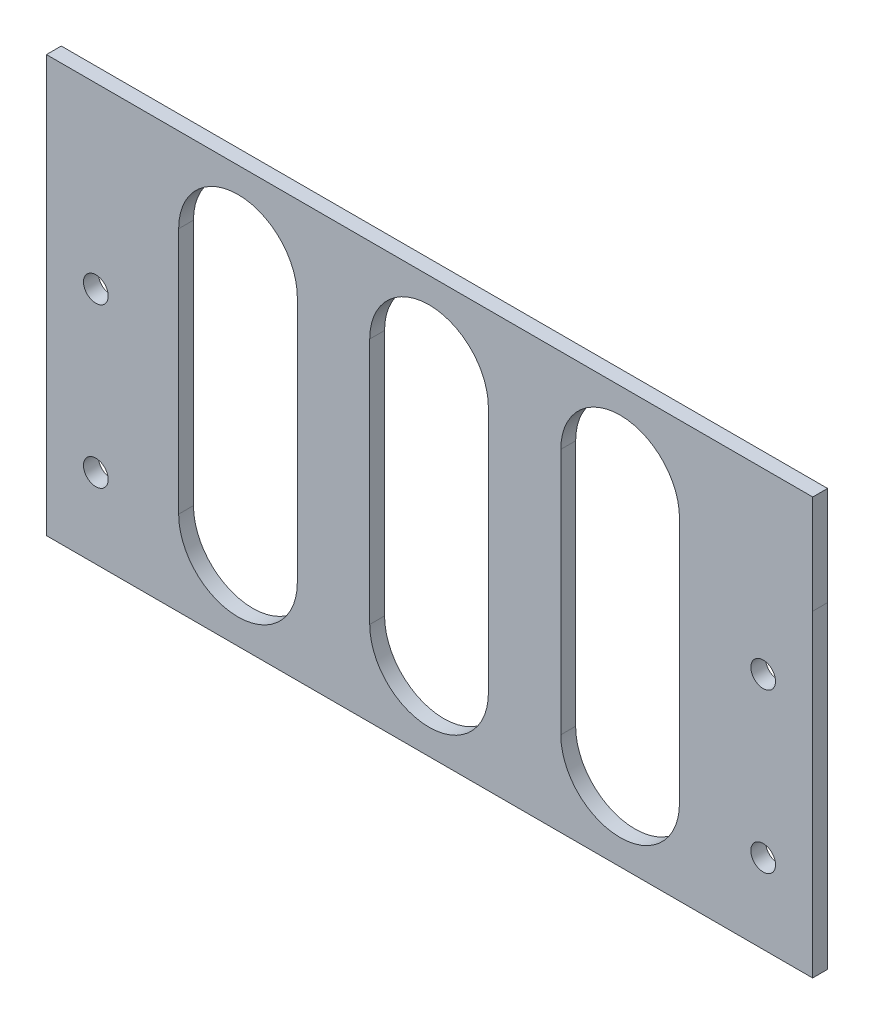
SolidWorks part; units mm, degrees
material "Custom Plastic"
ref_plane "Plan de face" through (0, 0, 0) normal (0, 0, 1) x (1, 0, 0)
ref_plane "Plan de dessus" through (0, 0, 0) normal (0, 1, 0) x (1, 0, 0)
ref_plane "Plan de droite" through (0, 0, 0) normal (1, 0, 0) x (0, 0, -1)
sketch "Esquisse2" plane through (0, 0, 0) normal (0, 1, 0) x (1, 0, 0)
  line L1 (-77.9251, 1.5) -> (77.0549, 1.5)
  line L2 (-77.9251, 1.5) -> (-77.9251, -1.5)
  line L3 (-77.9251, -1.5) -> (77.0549, -1.5)
  line L4 (77.0549, 1.5) -> (77.0549, -1.5)
  line L5 (-77.9251, 1.5) -> (77.0549, -1.5) construction
  line L6 (-77.9251, -1.5) -> (77.0549, 1.5) construction
  point P4 (-0.4351, 0)
  dimension "D1" = 3
  dimension "D2" = 154.98
extrude "Boss.-Extru.1" add sketch "Esquisse2" along normal up to surface (64.27 mm away)
sketch "Esquisse3" plane through (0, 0, 1.5) normal (0, 0, 1) x (1, 0, 0)
  line L0 (-54.572, 48.2025) -> (-50054.572, 48.2025) construction
  line L1 (67.0549, 84.4923) -> (67.0549, -49694.1144) construction
  line L4 (-67.9251, 32.135) -> (-77.9251, 32.135) construction
  line L5 (-77.9251, 64.27) -> (-77.9251, 0) construction
  line L7 (-77.9251, 64.27) -> (77.0549, 64.27) construction
  line L8 (77.0549, 32.135) -> (67.0549, 32.135) construction
  line L11 (-77.9251, 0) -> (77.0549, 0) construction
  line L12 (-67.9251, 64.27) -> (-67.9251, 32.135) construction
  line L13 (-67.9251, 32.135) -> (-67.9251, 0) construction
  line L14 (-54.572, 16.0675) -> (-50054.572, 16.0675) construction
  line L16 (77.0549, 64.27) -> (77.0549, 0) construction
  circle A2 centre (-67.9251, 16.0675) radius 2.5
  circle A3 centre (-67.9251, 48.2025) radius 2.5
  circle A4 centre (67.0549, 48.2025) radius 2.5
  circle A5 centre (67.0549, 16.0675) radius 2.5
  point P33 (-67.9251, 48.2025)
  point P35 (-67.9251, 16.0675)
  dimension "D2" = 5
  dimension "D1" = 10
extrude "Enlèv. mat.-Extru.1" cut sketch "Esquisse3" against normal through all
sketch "Esquisse4" plane through (0, 0, 1.5) normal (0, 0, 1) x (1, 0, 0)
  line L0 (-41.6801, 47.135) -> (-41.6801, 17.135)
  line L1 (-36.6801, 17.135) -> (-36.6801, 47.135)
  line L2 (-36.6801, 32.135) -> (-41.6801, 32.135) construction
  line L3 (-41.6801, 17.135) -> (-36.6801, 17.135) construction
  line L4 (-41.6801, 47.135) -> (-36.6801, 47.135) construction
  line L5 (-2.9351, 47.135) -> (-2.9351, 17.135)
  line L6 (2.0649, 17.135) -> (2.0649, 47.135)
  line L7 (2.0649, 32.135) -> (-2.9351, 32.135) construction
  line L8 (-2.9351, 17.135) -> (2.0649, 17.135) construction
  line L9 (-2.9351, 47.135) -> (2.0649, 47.135) construction
  line L10 (35.8099, 47.135) -> (35.8099, 17.135)
  line L11 (40.8099, 17.135) -> (40.8099, 47.135)
  line L12 (40.8099, 32.135) -> (35.8099, 32.135) construction
  line L13 (35.8099, 17.135) -> (40.8099, 17.135) construction
  line L14 (35.8099, 47.135) -> (40.8099, 47.135) construction
  line L15 (-77.9251, 64.27) -> (-77.9251, 74.27) construction
  line L16 (-77.9251, 74.27) -> (-39.1801, 74.27) construction
  line L17 (-39.1801, 74.27) -> (-0.4351, 74.27) construction
  line L18 (-0.4351, 74.27) -> (38.3099, 74.27) construction
  line L19 (38.3099, 74.27) -> (77.0549, 74.27) construction
  line L20 (77.0549, 74.27) -> (77.0549, 64.27) construction
  line L21 (-39.1801, 74.27) -> (-39.1801, -49925.73) construction
  line L22 (-0.4351, 75.8687) -> (-0.4351, -49924.1313) construction
  line L23 (38.3099, 74.27) -> (38.3099, -49925.73) construction
  line L24 (77.0549, 32.135) -> (83.5571, 32.135) construction
  line L26 (77.0549, 64.27) -> (77.0549, 0) construction
  arc A0 (-36.6801, 47.135) -> (-41.6801, 47.135) centre (-39.1801, 47.135) ccw
  arc A1 (-36.6801, 17.135) -> (-41.6801, 17.135) centre (-39.1801, 17.135) cw
  arc A2 (2.0649, 47.135) -> (-2.9351, 47.135) centre (-0.4351, 47.135) ccw
  arc A3 (2.0649, 17.135) -> (-2.9351, 17.135) centre (-0.4351, 17.135) cw
  arc A4 (40.8099, 47.135) -> (35.8099, 47.135) centre (38.3099, 47.135) ccw
  arc A5 (40.8099, 17.135) -> (35.8099, 17.135) centre (38.3099, 17.135) cw
  point P8 (-39.1801, 32.135)
  point P39 (-0.4351, 32.135)
  point P40 (38.3099, 32.135)
  point P44 (77.0549, 32.135)
  dimension "D2" = 5
  dimension "D1" = 5
  dimension "D3" = 5
  dimension "D4" = 10
  dimension "D5" = 30
extrude "Enlèv. mat.-Extru.2" cut sketch "Esquisse4" against normal through all
sketch "Sketch1" plane through (0, 0, 1.5) normal (0, 0, 1) x (1, 0, 0)
  line L1 (-77.9251, 64.27) -> (77.0793, 64.27)
  line L2 (-77.9251, 64.27) -> (-77.9251, 84.27)
  line L3 (-77.9251, 84.27) -> (77.0793, 84.27)
  line L4 (77.0793, 64.27) -> (77.0793, 84.27)
  dimension "D1" = 20
extrude "Boss-Extrude1" add sketch "Sketch1" against normal blind 3
sketch "Sketch2" plane through (0, 0, 1.5) normal (0, 0, 1) x (1, 0, 0)
  line L0 (-39.1801, 17.135) -> (-39.1801, 67.135) construction
  line L1 (-39.1801, 67.135) -> (-39.1801, 17.135) construction
  line L2 (-27.1801, 67.135) -> (-27.1801, 17.135)
  line L3 (-51.1801, 67.135) -> (-51.1801, 17.135)
  line L4 (-12.5301, 67.135) -> (-12.5301, 17.135)
  line L5 (11.4699, 67.135) -> (11.4699, 17.135)
  line L6 (-0.5301, 67.135) -> (-0.5301, 17.135) construction
  line L7 (26.1199, 67.135) -> (26.1199, 17.135)
  line L8 (50.1199, 67.135) -> (50.1199, 17.135)
  line L9 (38.1199, 67.135) -> (38.1199, 17.135) construction
  arc A0 (-27.1801, 67.135) -> (-51.1801, 67.135) centre (-39.1801, 67.135) ccw
  arc A1 (-51.1801, 17.135) -> (-27.1801, 17.135) centre (-39.1801, 17.135) ccw
  arc A2 (11.4699, 67.135) -> (-12.5301, 67.135) centre (-0.5301, 67.135) ccw
  arc A3 (-12.5301, 17.135) -> (11.4699, 17.135) centre (-0.5301, 17.135) ccw
  arc A4 (50.1199, 67.135) -> (26.1199, 67.135) centre (38.1199, 67.135) ccw
  arc A5 (26.1199, 17.135) -> (50.1199, 17.135) centre (38.1199, 17.135) ccw
  point P3 (-39.1801, 42.135)
  point P12 (-0.5301, 42.135)
  point P19 (38.1199, 42.135)
  dimension "D2" = 12
  dimension "D1" = 50
  dimension "D3" = 3
extrude "Cut-Extrude1" cut sketch "Sketch2" against normal blind 10
